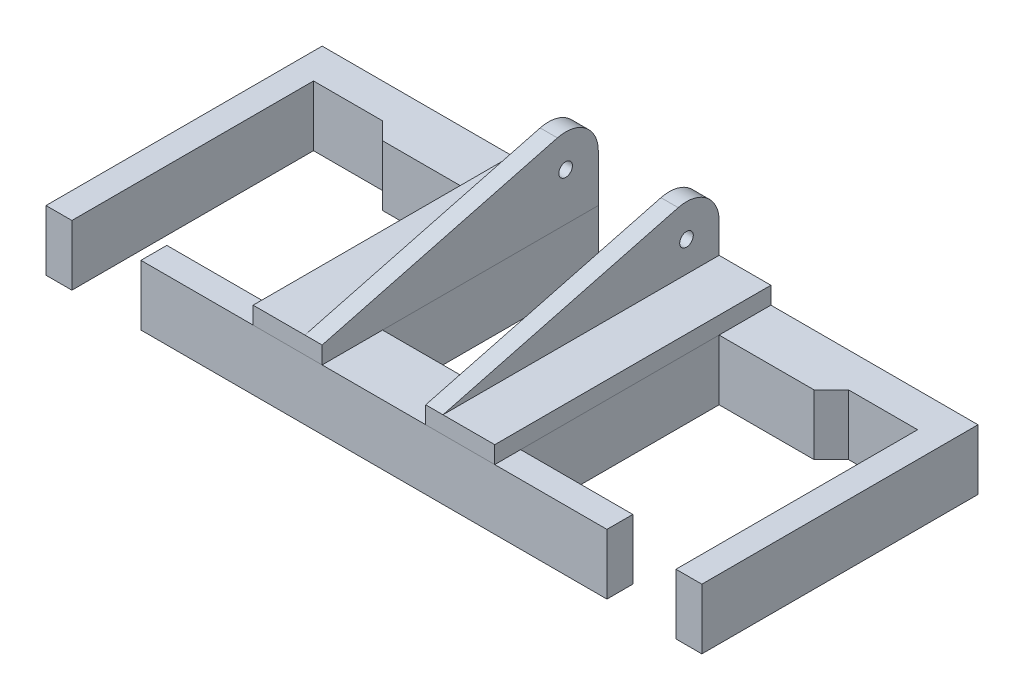
SolidWorks part; units mm, degrees
ref_plane "Front Plane" through (0, 0, 0) normal (0, 0, 1) x (1, 0, 0)
ref_plane "Top Plane" through (0, 0, 0) normal (0, 1, 0) x (1, 0, 0)
ref_plane "Right Plane" through (0, 0, 0) normal (1, 0, 0) x (0, 0, -1)
sketch "Sketch1" plane through (0, 0, 0) normal (0, 1, 0) x (1, 0, 0)
  line L0 (-19.05, 0) -> (-19.05, -79.375)
  line L1 (-19.05, -79.375) -> (19.05, -79.375)
  line L2 (19.05, -79.375) -> (19.05, 0)
  line L3 (19.05, 0) -> (120.65, 0)
  line L4 (-120.65, 0) -> (-120.65, -101.6)
  line L5 (120.65, 0) -> (120.65, -101.6)
  line L6 (-44.45, -19.05) -> (-79.375, -19.05)
  line L7 (-120.65, -101.6) -> (-111.125, -101.6)
  line L8 (-111.125, -12.7) -> (-111.125, -101.6)
  line L9 (-120.65, 0) -> (-19.05, 0)
  line L10 (44.45, -19.05) -> (79.375, -19.05)
  line L11 (-44.45, -92.075) -> (-85.725, -92.075)
  line L12 (-85.725, -92.075) -> (-85.725, -101.6)
  line L13 (44.45, -92.075) -> (85.725, -92.075)
  line L14 (85.725, -92.075) -> (85.725, -101.6)
  line L15 (-85.725, -101.6) -> (85.725, -101.6)
  line L16 (111.125, -101.6) -> (120.65, -101.6)
  line L17 (111.125, -12.7) -> (111.125, -101.6)
  line L18 (-44.45, -19.05) -> (-44.45, -92.075)
  line L19 (-79.375, -19.05) -> (-85.725, -12.7)
  line L20 (44.45, -92.075) -> (44.45, -19.05)
  line L21 (-85.725, -12.7) -> (-111.125, -12.7)
  line L22 (79.375, -19.05) -> (85.725, -12.7)
  line L23 (85.725, -12.7) -> (111.125, -12.7)
  point P4 (0, 0)
  point P8 (74.3817, -19.05)
  point P10 (0, -79.375)
  dimension "D1" = 38.1
  dimension "D2" = 101.6
  dimension "D3" = 101.6
  dimension "D4" = 9.525
  dimension "D5" = 19.05
  dimension "D6" = 25.4
  dimension "D7" = 22.225
  dimension "D8" = 9.525
  dimension "D9" = 12.7
  dimension "D10" = 25.4
  dimension "D11" = 25.4
  dimension "D12" = 19.05
  dimension "D13" = 9.525
  dimension "D14" = 45
extrude "Boss-Extrude1" add sketch "Sketch1" along normal blind 22.225
sketch "Sketch5" plane through (0, 0, 0) normal (0, 0, -1) x (-1, 0, 0)
  line L0 (-19.05, 22.225) -> (-19.05, 73.025)
  line L1 (-19.05, 73.025) -> (-25.4, 73.025)
  line L2 (-25.4, 73.025) -> (-25.4, 28.575)
  line L3 (-25.4, 28.575) -> (-44.45, 28.575)
  line L4 (-44.45, 28.575) -> (-44.45, 22.225)
  line L5 (-120.65, 22.225) -> (-19.05, 22.225) construction
  line L6 (-44.45, 22.225) -> (-19.05, 22.225)
  line L7 (19.05, 22.225) -> (44.45, 22.225)
  line L8 (19.05, 22.225) -> (120.65, 22.225) construction
  line L9 (44.45, 22.225) -> (44.45, 28.575)
  line L10 (44.45, 28.575) -> (25.4, 28.575)
  line L11 (25.4, 28.575) -> (25.4, 73.025)
  line L12 (25.4, 73.025) -> (19.05, 73.025)
  line L13 (19.05, 73.025) -> (19.05, 22.225)
  point P16 (-28.9197, 73.025)
  dimension "D1" = 25.4
  dimension "D2" = 50.8
  dimension "D3" = 6.35
extrude "Boss-Extrude2" add sketch "Sketch5" against normal up to surface (101.6 mm away) separate body up to face at (0, 11.1125, 101.6)
sketch "Sketch6" plane through (0, 0, 0) normal (1, 0, 0) x (0, 0, -1)
  line L0 (0, 0) -> (-101.6, 0) construction
  line L1 (-101.6, 28.575) -> (-15.0467, 51.2943)
  line L2 (0, 28.575) -> (0, 73.025) construction
  line L3 (0, 39.6875) -> (13.3964, 39.6875)
  line L4 (13.3964, 39.6875) -> (13.3964, 119.6902)
  line L5 (13.3964, 119.6902) -> (-183.8801, 119.6902)
  line L6 (-183.8801, 119.6902) -> (-101.6, 28.575)
  circle A0 centre (-12, 39.6875) radius 39.6875 construction
  arc A1 (-15.0467, 51.2943) -> (0, 39.6875) centre (-12, 39.6875) cw
  circle A2 centre (-12, 39.6875) radius 2.5
  point P14 (-183.8801, 119.6902)
  dimension "D1" = 79.375
  dimension "D2" = 12
  dimension "D3" = 5
extrude "Cut-Extrude2" cut sketch "Sketch6" against normal through all both and the other way through all
